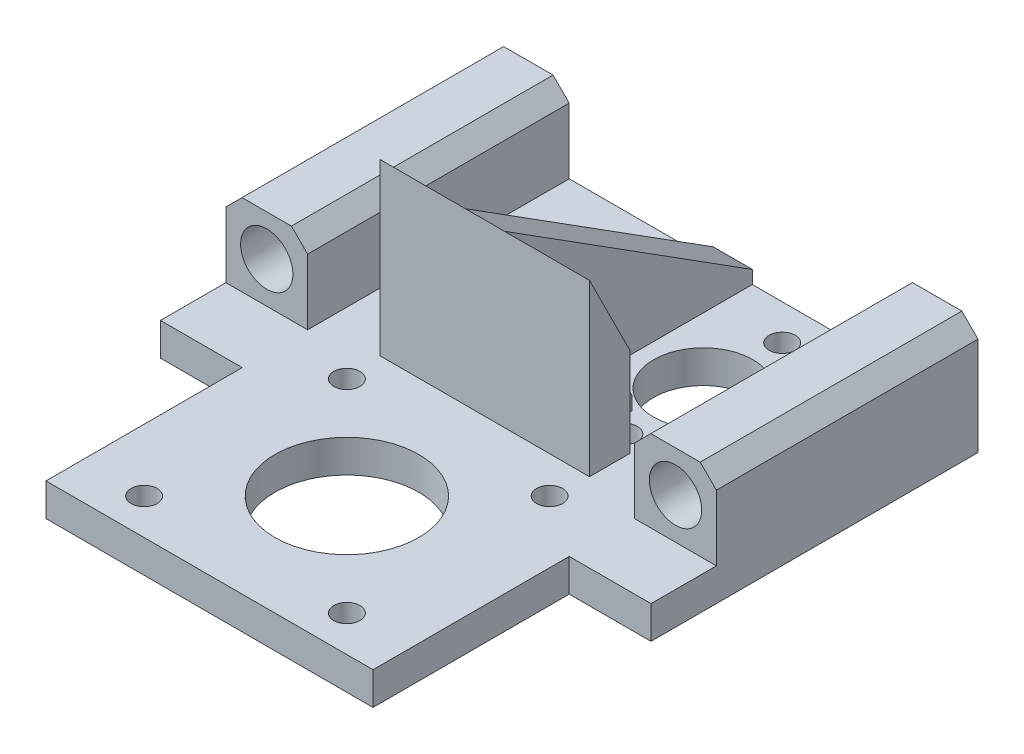
SolidWorks part; units mm, degrees
ref_plane "Front Plane" through (0, 0, 0) normal (0, 0, 1) x (1, 0, 0)
ref_plane "Top Plane" through (0, 0, 0) normal (0, 1, 0) x (1, 0, 0)
ref_plane "Right Plane" through (0, 0, 0) normal (1, 0, 0) x (0, 0, -1)
sketch "Sketch1" plane through (0, 0, 0) normal (0, 1, 0) x (1, 0, 0)
  line L0 (0, 32.5) -> (75, 32.5) construction
  line L1 (0, 0) -> (75, 0)
  line L2 (0, 0) -> (0, 50)
  line L3 (0, 50) -> (75, 50)
  line L4 (75, 0) -> (75, 50)
  line L5 (37.5, 50) -> (37.5, 0) construction
  line L6 (37.5, 32.5) -> (24.5, 32.5) construction
  line L7 (37.5, 32.5) -> (50.5, 32.5) construction
  circle A0 centre (24.5, 32.5) radius 5.1
  circle A1 centre (50.5, 32.5) radius 7.6
  point P15 (37.5, 32.5)
  dimension "D2" = 10.2
  dimension "D6" = 15.2
  dimension "D1" = 26
  dimension "D3" = 75
  dimension "D4" = 50
  dimension "D5" = 17.5
extrude "Boss-Extrude1" add sketch "Sketch1" along normal blind 5
sketch "Sketch2" plane through (0, 5, 0) normal (0, 1, 0) x (1, 0, 0)
  line L4 (0, 50) -> (12.5, 50)
  line L5 (0, 50) -> (0, 10)
  line L6 (0, 10) -> (12.5, 10)
  line L7 (12.5, 50) -> (12.5, 10)
  line L8 (75, 50) -> (62.5, 50)
  line L9 (75, 50) -> (75, 10)
  line L10 (75, 10) -> (62.5, 10)
  line L11 (62.5, 50) -> (62.5, 10)
  dimension "D1" = 40
  dimension "D3" = 12.5
extrude "Boss-Extrude2" add sketch "Sketch2" along normal blind 12.5
sketch "Sketch3" plane through (0, 0, -50) normal (0, 0, -1) x (-1, 0, 0)
  line L0 (-37.5, 0) -> (-37.5, 50000) construction
  line L1 (-75, 0) -> (0, 0) construction
  line L2 (-62.5, 5) -> (-12.5, 5) construction
  line L3 (-72.5251, 17.5) -> (-75, 17.5)
  line L4 (-75, 17.5) -> (-62.5, 17.5) construction
  line L5 (-75, 17.5) -> (-75, 15.0251)
  line L6 (-75, 17.5) -> (-75, 0) construction
  line L7 (-75, 15.0251) -> (-72.5251, 17.5)
  line L8 (-62.5, 17.5) -> (-64.9749, 17.5)
  line L9 (-64.9749, 17.5) -> (-62.5, 15.0251)
  line L10 (-62.5, 17.5) -> (-62.5, 5) construction
  line L11 (-62.5, 15.0251) -> (-62.5, 17.5)
  line L12 (-68.75, 17.5) -> (-68.75, 0) construction
  line L13 (-62.5, 11.25) -> (-75, 11.25) construction
  line L14 (-12.5, 11.25) -> (0, 11.25) construction
  line L15 (-6.25, 17.5) -> (-6.25, 0) construction
  line L16 (-12.5, 15.0251) -> (-12.5, 17.5)
  line L17 (-10.0251, 17.5) -> (-12.5, 15.0251)
  line L18 (-12.5, 17.5) -> (-10.0251, 17.5)
  line L19 (0, 15.0251) -> (-2.4749, 17.5)
  line L20 (0, 17.5) -> (0, 15.0251)
  line L21 (-2.4749, 17.5) -> (0, 17.5)
  circle A0 centre (-68.75, 11.25) radius 4
  circle A1 centre (-6.25, 11.25) radius 4
  point P4 (-37.5, 0)
  point P7 (-37.5, 5)
  dimension "D1" = 8
  dimension "D2" = 3.5
extrude "Cut-Extrude1" cut sketch "Sketch3" against normal through all
sketch "Sketch4" plane through (0, 5, 0) normal (0, 1, 0) x (1, 0, 0)
  line L0 (0, 0) -> (75, 0) construction
  line L1 (62.5, 0) -> (12.5, 0)
  line L2 (62.5, 0) -> (62.5, -30)
  line L3 (62.5, -30) -> (12.5, -30)
  line L4 (12.5, 0) -> (12.5, -30)
  line L5 (37.5, 50) -> (37.5, 0) construction
  line L6 (62.5, 50) -> (12.5, 50) construction
  point P10 (37.5, 0)
  dimension "D1" = 50
  dimension "D2" = 30
extrude "Boss-Extrude3" add sketch "Sketch4" against normal up to surface (5 mm away) up to face at (24.5, 0, -27.4)
sketch "Sketch5" plane through (0, 5, 0) normal (0, 1, 0) x (1, 0, 0)
  line L0 (37.5, -30) -> (37.5, 50) construction
  line L1 (12.5, -30) -> (62.5, -30) construction
  line L2 (62.5, 50) -> (12.5, 50) construction
  line L3 (58.5, -9) -> (16.5, -9) construction
  circle A0 centre (22, -24.5) radius 2
  circle A1 centre (22, 6.5) radius 2
  circle A2 centre (53, 6.5) radius 2
  circle A3 centre (53, -24.5) radius 2
  circle A4 centre (37.5, -9) radius 11
  point P8 (37.5, -9)
  dimension "D5" = 4
  dimension "D6" = 22
  dimension "D1" = 42
  dimension "D2" = 21
  dimension "D3" = 15.5
  dimension "D4" = 15.5
extrude "Cut-Extrude2" cut sketch "Sketch5" against normal through all
sketch "Sketch6" plane through (0, 5, 0) normal (0, 1, 0) x (1, 0, 0)
  line L0 (37.5, -30) -> (37.5, 12.1) construction
  line L1 (12.5, -30) -> (62.5, -30) construction
  line L3 (53.5, 12.1) -> (21.5, 12.1)
  line L4 (53.5, 12.1) -> (53.5, 24.1)
  line L5 (53.5, 24.1) -> (21.5, 24.1)
  line L6 (21.5, 12.1) -> (21.5, 24.1)
  point P9 (37.5, 12.1)
  dimension "D1" = 42.1
  dimension "D2" = 12
  dimension "D3" = 32
extrude "Boss-Extrude4" add sketch "Sketch6" along normal blind 2
sketch "Sketch8" plane through (53.5, 0, 0) normal (1, 0, 0) x (0, 0, -1)
  line L0 (24.1, 7) -> (12.1, 7)
  line L1 (12.1, 7) -> (12.1, 31)
  line L2 (12.1, 31) -> (24.1, 7)
  dimension "D1" = 24
extrude "Boss-Extrude6" add sketch "Sketch8" against normal up to surface (32 mm away) up to face at (21.5, 6, -18.1)
sketch "Sketch9" plane through (0, 5, 0) normal (0, 1, 0) x (1, 0, 0)
  line L0 (62.5, 50) -> (12.5, 50) construction
  line L1 (40.5, 50) -> (34.5, 50)
  line L2 (40.5, 50) -> (40.5, 24.1)
  line L3 (40.5, 24.1) -> (34.5, 24.1)
  line L4 (34.5, 50) -> (34.5, 24.1)
  line L5 (53.5, 24.1) -> (21.5, 24.1) construction
  line L6 (37.5, 50) -> (37.5, -138.6407) construction
  point P10 (37.5, 50)
  point P11 (37.5, 50)
  dimension "D1" = 6
extrude "Boss-Extrude7" add sketch "Sketch9" along normal up to vertex (2 mm away) up to point (21.5, 7, -24.1)
sketch "Sketch10" plane through (34.5, 0, 0) normal (-1, 0, 0) x (0, 0, 1)
  line L0 (-50, 7) -> (-12.1, 31)
  line L1 (-12.1, 31) -> (-24.1, 7)
  line L2 (-24.1, 7) -> (-50, 7)
  line L3 (-12.1, 31) -> (-24.1, 7) construction
extrude "Boss-Extrude8" add sketch "Sketch10" against normal up to surface (6 mm away) up to face at (40.5, 6, -37.05)
sketch "Sketch11" plane through (0, 5, 5) normal (0, 1, 0) x (1, 0, 0)
  line L0 (50.5, 29.9) -> (50.5, 45.1) construction
  line L1 (24.5, 42.6) -> (24.5, 32.4) construction
  line L2 (29.6, 37.5) -> (19.4, 37.5) construction
  line L3 (29.6, 37.5) -> (19.4, 37.5) construction
  line L5 (50.5, 29.9) -> (50.5, 45.1) construction
  circle A0 centre (50.5, 37.5) radius 7.6 construction
  circle A1 centre (50.5, 25.43) radius 2
  circle A2 centre (50.5, 49.565) radius 2
  circle A3 centre (24.5, 37.5) radius 5.1 construction
  circle A6 centre (24.5, 45.5) radius 1.5
  circle A7 centre (16.5, 37.5) radius 1.5
  circle A8 centre (32.5, 37.5) radius 1.5
  circle A9 centre (24.5, 29.5) radius 1.5
  point P5 (24.5, 37.5)
  point P10 (50.5, 37.5)
  point P20 (24.5, 37.5)
  dimension "D3" = 4
  dimension "D6" = 3
  dimension "D1" = 12.065
  dimension "D2" = 12.07
  dimension "D4" = 8
  dimension "D5" = 8
extrude "Cut-Extrude3" cut sketch "Sketch11" against normal through all both and the other way through all
sketch "Sketch13" plane through (0, 5, 0) normal (0, 1, 0) x (1, 0, 0)
  line L1 (53.5, 24.1) -> (48, 24.1)
  line L2 (53.5, 24.1) -> (53.5, 22.4258)
  line L3 (53.5, 22.4258) -> (48, 22.4258)
  line L4 (48, 24.1) -> (48, 22.4258)
  circle A0 centre (50.5, 20.43) radius 3.7
  circle A1 centre (24.5, 24.5) radius 2.75
  line M35 (53.5, 24.1) -> (53.5, 12.1)
  dimension "D1" = 5.5
  dimension "D2" = 7.4
  dimension "D3" = 5.5
  dimension "D4" = 1.6742
extrude "Cut-Extrude4" cut sketch "Sketch13" along normal through all contours A0 L2 M35 | A1
equation "\"8mm hole\" = 8mm"
equation "\"22mm hole\"= 22mm"
equation "\"D6@Sketch5\"= \"22mm hole\""
equation "\"D1@Sketch3\"= \"8mm hole\""
